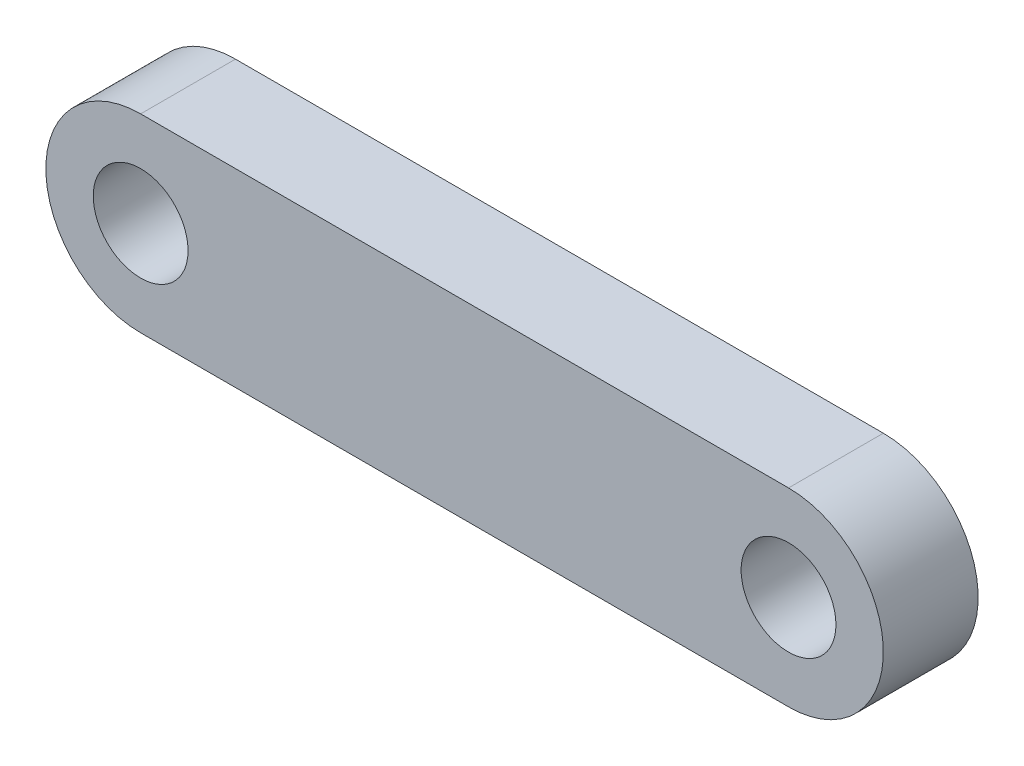
SolidWorks part; units mm, degrees
material "Thornel Mat VMA"
ref_plane "前视基准面" through (0, 0, 0) normal (0, 0, 1) x (1, 0, 0)
ref_plane "上视基准面" through (0, 0, 0) normal (0, 1, 0) x (1, 0, 0)
ref_plane "右视基准面" through (0, 0, 0) normal (1, 0, 0) x (0, 0, -1)
sketch "草图1" plane through (0, 0, 0) normal (0, 0, 1) x (1, 0, 0)
  line L0 (0, 0) -> (20.5, 0) construction
  line L2 (0, 3) -> (20.5, 3)
  line L3 (0, -3) -> (20.5, -3)
  arc A0 (0, 3) -> (0, -3) centre (0, 0) ccw
  arc A1 (20.5, -3) -> (20.5, 3) centre (20.5, 0) ccw
  circle A2 centre (0, 0) radius 1.5
  circle A3 centre (20.5, 0) radius 1.5
  point P5 (10.25, 0)
  dimension "D1" = 3
  dimension "D3" = 3
  dimension "D4" = 3
  dimension "D2" = 20.5
extrude "凸台-拉伸1" add sketch "草图1" along normal blind 3
